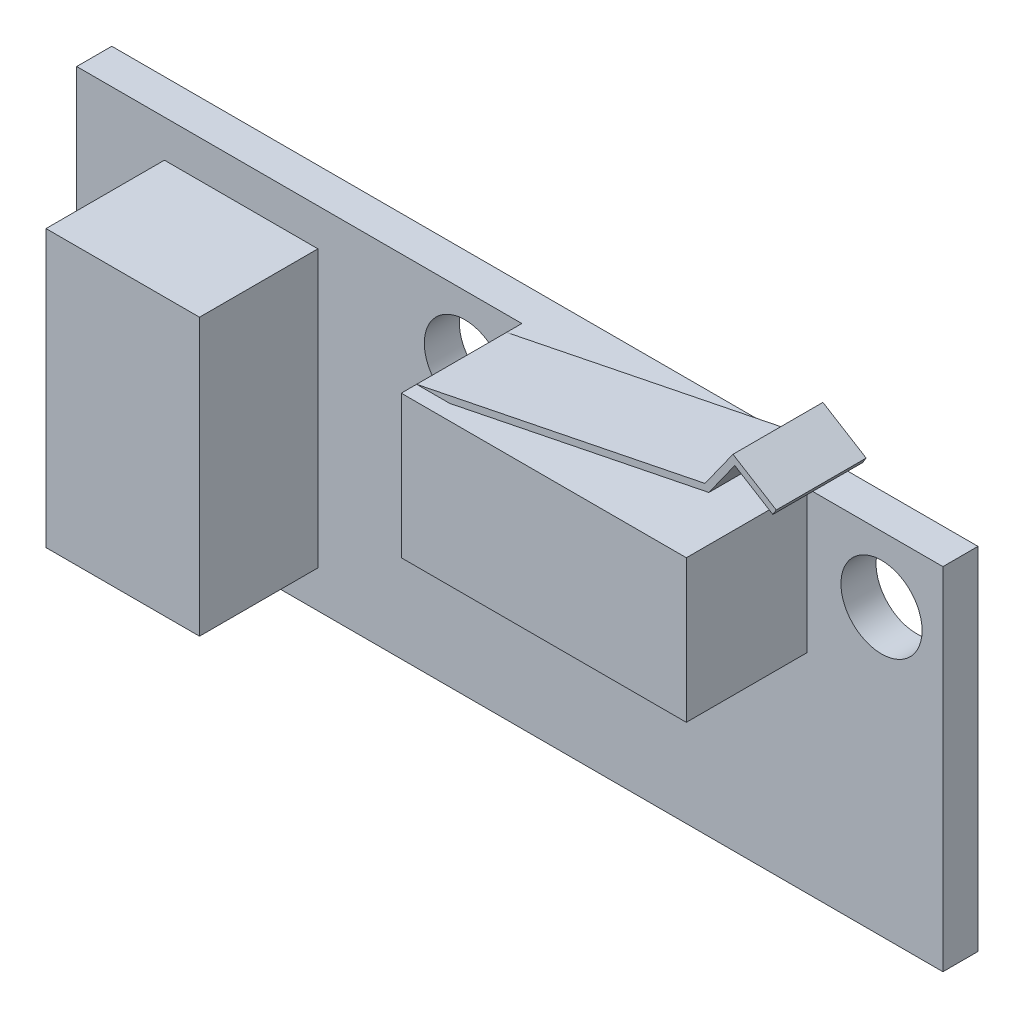
SolidWorks part; units mm, degrees
ref_plane "Front Plane" through (0, 0, 0) normal (0, 0, 1) x (1, 0, 0)
ref_plane "Top Plane" through (0, 0, 0) normal (0, 1, 0) x (1, 0, 0)
ref_plane "Right Plane" through (0, 0, 0) normal (1, 0, 0) x (0, 0, -1)
sketch "Sketch1" plane through (0, 0, 0) normal (0, 0, 1) x (1, 0, 0)
  line L1 (-19.75, -8) -> (19.75, -8)
  line L2 (-19.75, -8) -> (-19.75, 8)
  line L3 (-19.75, 8) -> (19.75, 8)
  line L4 (19.75, -8) -> (19.75, 8)
  line L5 (-19.75, -8) -> (19.75, 8) construction
  line L6 (-19.75, 8) -> (19.75, -8) construction
  point P0 (0, 0)
  dimension "D1" = 16
  dimension "D2" = 39.5
extrude "Boss-Extrude1" add sketch "Sketch1" along normal blind 1.6
sketch "Sketch2" plane through (0, 0, 1.6) normal (0, 0, 1) x (1, 0, 0)
  line L0 (-19.75, 5) -> (19.75, 5) construction
  line L1 (-19.75, 8) -> (-19.75, -8) construction
  line L2 (19.75, -8) -> (19.75, 8) construction
  line L3 (19.75, 8) -> (-19.75, 8) construction
  circle A0 centre (16.95, 5) radius 1.85
  circle A1 centre (-2.05, 5) radius 1.85
  point P12 (-3.2819, 5)
  dimension "D1" = 3.7
  dimension "D2" = 19
  dimension "D3" = 3
  dimension "D4" = 2.8
extrude "Cut-Extrude1" cut sketch "Sketch2" against normal blind 1.6
sketch "Sketch3" plane through (0, 0, 1.6) normal (0, 0, 1) x (1, 0, 0)
  line L0 (19.75, 8) -> (-19.75, 8) construction
  line L1 (0.55, 8) -> (13.55, 8)
  line L2 (0.55, 8) -> (0.55, 1.5)
  line L3 (0.55, 1.5) -> (13.55, 1.5)
  line L4 (13.55, 8) -> (13.55, 1.5)
  line L5 (19.75, -8) -> (19.75, 8) construction
  dimension "D1" = 13
  dimension "D2" = 6.5
  dimension "D3" = 6.2
extrude "Boss-Extrude2" add sketch "Sketch3" along normal blind 5.5
sketch "Sketch4" plane through (0, 0, 7.1) normal (0, 0, 1) x (1, 0, 0)
  line L0 (0.55, 8) -> (13.7005, 10.6612)
  line L1 (13.7005, 10.6612) -> (14.9774, 12.45)
  line L2 (14.9774, 12.45) -> (16.95, 11.2364)
  line L3 (16.95, 11.2364) -> (16.7928, 10.9809)
  line L4 (16.7928, 10.9809) -> (15.0588, 12.0477)
  line L5 (15.0588, 12.0477) -> (13.876, 10.3906)
  line L6 (13.876, 10.3906) -> (2.0625, 8)
  line L7 (13.55, 8) -> (0.55, 8) construction
  line L8 (2.0625, 8) -> (0.55, 8)
  line L9 (13.876, 10.3906) -> (16.7928, 10.9809) construction
  line L10 (15.0588, 12.0477) -> (15.3344, 10.6858) construction
  point P11 (14.4674, 11.2192)
  dimension "D1" = 0.3
  dimension "D2" = 2.8
  dimension "D3" = 0.3
  dimension "D4" = 0.3
  dimension "D5" = 3.3
  dimension "D6" = 1.8
  dimension "D7" = 4.45
extrude "Boss-Extrude3" add sketch "Sketch4" against normal up to surface (5.5 mm away) up to face at (-0.2, 5, 1.6)
sketch "Sketch5" plane through (0, 8, 0) normal (0, 1, 0) x (1, 0, 0)
  line L1 (0.55, -7.1) -> (19.8151, -7.1)
  line L2 (0.55, -7.1) -> (0.55, -6.4)
  line L3 (0.55, -6.4) -> (19.8151, -6.4)
  line L4 (19.8151, -7.1) -> (19.8151, -6.4)
  line L5 (0.55, -1.6) -> (19.8151, -1.6)
  line L6 (0.55, -1.6) -> (0.55, -2.3)
  line L7 (0.55, -2.3) -> (19.8151, -2.3)
  line L8 (19.8151, -1.6) -> (19.8151, -2.3)
  dimension "D1" = 4.1
extrude "Cut-Extrude2" cut sketch "Sketch5" along normal blind 14.5
sketch "Sketch6" plane through (0, 0, 1.6) normal (0, 0, 1) x (1, 0, 0)
  line L0 (-19.75, 0) -> (19.75, 0) construction
  line L1 (-19.75, 8) -> (-19.75, -8) construction
  line L2 (19.75, -8) -> (19.75, 8) construction
  line L4 (-15.75, -6.3) -> (-8.75, -6.3)
  line L5 (-15.75, -6.3) -> (-15.75, 6.3)
  line L6 (-15.75, 6.3) -> (-8.75, 6.3)
  line L7 (-8.75, -6.3) -> (-8.75, 6.3)
  line L8 (-15.75, -6.3) -> (-8.75, 6.3) construction
  line L9 (-15.75, 6.3) -> (-8.75, -6.3) construction
  point P6 (-12.25, 0)
  dimension "D1" = 7
  dimension "D2" = 12.6
  dimension "D3" = 4
extrude "Boss-Extrude4" add sketch "Sketch6" along normal blind 5.4
